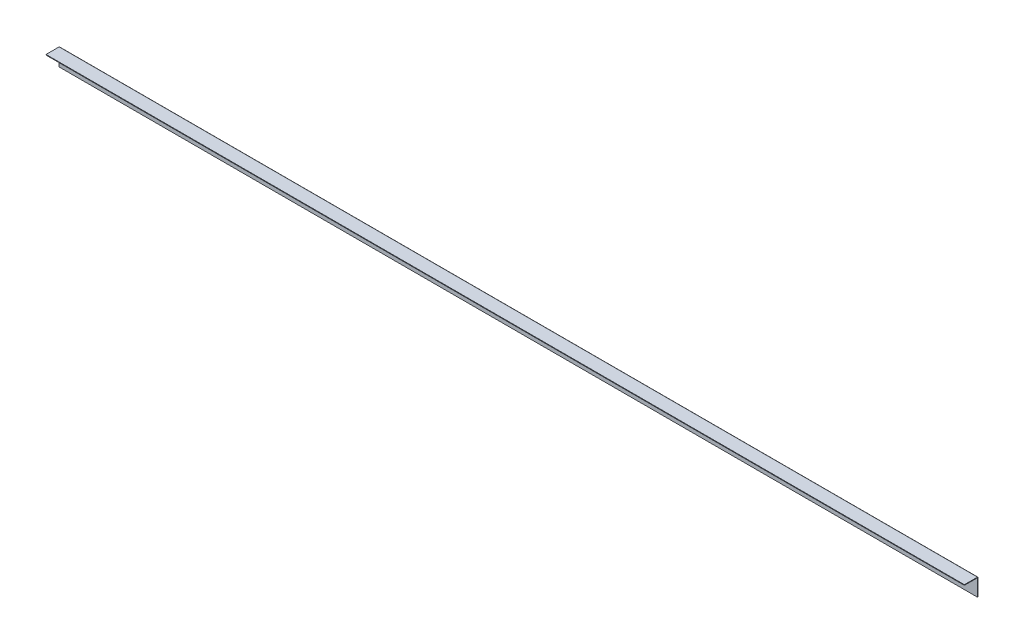
SolidWorks part; units mm, degrees
ref_plane "Front Plane" through (0, 0, 0) normal (0, 0, 1) x (1, 0, 0)
ref_plane "Top Plane" through (0, 0, 0) normal (0, 1, 0) x (1, 0, 0)
ref_plane "Right Plane" through (0, 0, 0) normal (1, 0, 0) x (0, 0, -1)
sketch "Sketch1" plane through (0, 0, 0) normal (1, 0, 0) x (0, 0, -1)
  line L0 (0, 0) -> (73, 0)
  line L1 (73, 0) -> (73, -93)
  line L2 (0, -3) -> (70, -3)
  line L3 (70, -3) -> (70, -93)
  line L4 (0, 0) -> (0, -3)
  line L5 (70, -93) -> (73, -93)
  dimension "D1" = 73
  dimension "D2" = 93
  dimension "D3" = 3
extrude "Boss-Extrude1" add sketch "Sketch1" along normal blind 4922
fillet "Fillet1" radius 3 2 edges at (2461, 0, -73) (2461, -3, -70)
equation "\"unequal_angleBar_Side_LT_3mm_length\"= 2922"
equation "\"D1@Boss-Extrude1\"= \"boxLength\" - 90 - 90 + 2"
equation "\"CarBeamWidth\"=700.0"
equation "\"WheelWidth\"=650.0"
equation "\"Wheel_FrontBoxDistance\"=1390.0"
equation "\"boxLength\"=5100.0"
equation "\"boxWidth\"=1930.0"
equation "\"MetalSheet_3mm_length\"=5030.0"
equation "\"MetalSheet_3mm_width\"=1923.0"
equation "\"MetalSheet_3mm_FloorCut_L_length\"=1764.0"
equation "\"MetalSheet_3mm_FloorCut_L_disdance\"=1665.0"
equation "\"MetalSheet_3mm_FloorCut_R_length\"=1764.0"
equation "\"MetalSheet_3mm_FloorCut_R_disdance\"=1665.0"
equation "\"indoorHeight\"=1940.0"
equation "\"indoorHeight_para\"=25.0"
equation "\"rearLightHeight_para\"=265.0"
equation "\"doorColumnBar_A_FR_3mm_length_Cut\"=2310.0"
equation "\"A\"=0.0"
equation "\"haveDoor_R\"=1"
equation "\"side_door_bottom_R_3mm_length\"=1934.0"
equation "\"side_door_bottom_R_3mm_toFrontDistance\"=1583.0"
equation "\"1Bar_Side_RF_3mm_length\"=1493.0"
equation "\"1Bar_Side_RB_3mm_length\"=1493.0"
equation "\"DoorSeparator_RF_3mm_withHinge_toFrontDistance\"=1673.0"
equation "\"DoorSeparator_RF_3mm_withHinge_exist\"=1"
equation "\"DoorSeparator_RB_3mm_withHinge_toFrontDistance\"=3427.0"
equation "\"DoorSeparator_RB_3mm_withHinge_exist\"=1"
equation "\"Door_R1_L_open_Single_toFrontDistance\"=2547.5"
equation "\"Door_R1_L_open_Single_exist\"=1"
equation "\"door_base_long7_R1_L_open_Single_height\"=1890.0"
equation "\"door_base_short7_R1_L_open_Single_height\"=1890.0"
equation "\"door_base_short7_R1_L_open_Single_width\"=864"
equation "\"Door_R1_R_open_Single_toFrontDistance\"=3422.0"
equation "\"Door_R1_R_open_Single_exist\"=1"
equation "\"door_base_long7_R1_R_open_Single_height\"=1890.0"
equation "\"door_base_short7_R1_R_open_Single_height\"=1890.0"
equation "\"door_base_short7_R1_R_open_Single_width\"=864"
equation "\"x\"=66.0"
equation "\"door_base_double_BL_height\"=1890.0"
equation "\"door_base_short7_BL_Single_height\"=1890.0"
equation "\"door_base_short7_BL_Single_width\"=864"
equation "\"door_base_long7_BR_Single_height\"=1890.0"
equation "\"door_base_short7_BR_Single_height\"=1890.0"
equation "\"door_base_short7_BR_Single_width\"=864"
equation "\"da\"=62.0"
equation "\"SquareTube_length\"=1923.0"
equation "\"channelSteel_length\"=5030.0"
equation "\"SquareTube_inFront_AvgDistance\"=285.0"
equation "\"SquareTube_inFront_TotalCount\"=5"
equation "\"SquareTube_inFront1_cutDepth50_R\"=0.5"
equation "\"SquareTube_inFront1_cutDepth50_L\"=0.5"
equation "\"SquareTube_inFront2_cutDepth50_R\"=0.5"
equation "\"SquareTube_inFront2_cutDepth50_L\"=0.5"
equation "\"SquareTube_inFront3_cutDepth50_R\"=0.5"
equation "\"SquareTube_inFront3_cutDepth50_L\"=0.5"
equation "\"SquareTube_inFront4_cutDepth50_R\"=0.5"
equation "\"SquareTube_inFront4_cutDepth50_L\"=0.5"
equation "\"SquareTube_inFront5_cutDepth50_R\"=50"
equation "\"SquareTube_inFront5_cutDepth50_L\"=50"
equation "\"SquareTube_inFront6_cutDepth50_R\"=50"
equation "\"SquareTube_inFront6_cutDepth50_L\"=50"
equation "\"SquareTube_inFront7_cutDepth50_R\"=50"
equation "\"SquareTube_inFront7_cutDepth50_L\"=50"
equation "\"SquareTube_inFront8_cutDepth50_R\"=50"
equation "\"SquareTube_inFront8_cutDepth50_L\"=50"
equation "\"SquareTube_inFront9_cutDepth50_R\"=50"
equation "\"SquareTube_inFront9_cutDepth50_L\"=50"
equation "\"SquareTube_inFront10_cutDepth50_R\"=50"
equation "\"SquareTube_inFront10_cutDepth50_L\"=50"
equation "\"SquareTube_inFront11_cutDepth50_R\"=50"
equation "\"SquareTube_inFront11_cutDepth50_L\"=50"
equation "\"SquareTube_inFront12_cutDepth50_R\"=50"
equation "\"SquareTube_inFront12_cutDepth50_L\"=50"
equation "\"SquareTube_inFront13_cutDepth50_R\"=50"
equation "\"SquareTube_inFront13_cutDepth50_L\"=50"
equation "\"SquareTube_inFront14_cutDepth50_R\"=50"
equation "\"SquareTube_inFront14_cutDepth50_L\"=50"
equation "\"SquareTube_inBack_AvgDistance\"=333.125"
equation "\"SquareTube_inBack_TotalCount\"=9"
equation "\"SquareTube_inBack1_cutDepth50_R\"=50"
equation "\"SquareTube_inBack1_cutDepth50_L\"=50"
equation "\"SquareTube_inBack2_cutDepth50_R\"=50"
equation "\"SquareTube_inBack2_cutDepth50_L\"=50"
equation "\"SquareTube_inBack3_cutDepth50_R\"=50"
equation "\"SquareTube_inBack3_cutDepth50_L\"=50"
equation "\"SquareTube_inBack4_cutDepth50_R\"=50"
equation "\"SquareTube_inBack4_cutDepth50_L\"=50"
equation "\"SquareTube_inBack5_cutDepth50_R\"=50"
equation "\"SquareTube_inBack5_cutDepth50_L\"=50"
equation "\"SquareTube_inBack6_cutDepth50_R\"=0.5"
equation "\"SquareTube_inBack6_cutDepth50_L\"=0.5"
equation "\"SquareTube_inBack7_cutDepth50_R\"=0.5"
equation "\"SquareTube_inBack7_cutDepth50_L\"=0.5"
equation "\"SquareTube_inBack8_cutDepth50_R\"=0.5"
equation "\"SquareTube_inBack8_cutDepth50_L\"=0.5"
